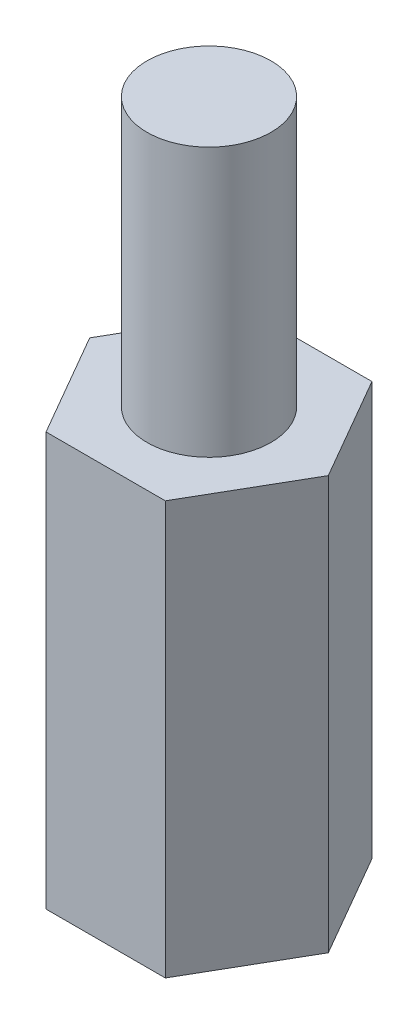
SolidWorks part; units mm, degrees
material "ﾅｲﾛﾝ 101"
ref_plane "正面" through (0, 0, 0) normal (0, 0, 1) x (1, 0, 0)
ref_plane "平面" through (0, 0, 0) normal (0, 1, 0) x (1, 0, 0)
ref_plane "右側面" through (0, 0, 0) normal (1, 0, 0) x (0, 0, -1)
sketch "ｽｹｯﾁ1" plane through (0, 0, 0) normal (0, 1, 0) x (1, 0, 0)
  line L1 (1.4434, -2.5) -> (2.8868, 0)
  line L2 (2.8868, 0) -> (1.4434, 2.5)
  line L3 (1.4434, 2.5) -> (-1.4434, 2.5)
  line L4 (-1.4434, 2.5) -> (-2.8868, 0)
  line L5 (-2.8868, 0) -> (-1.4434, -2.5)
  line L6 (-1.4434, -2.5) -> (1.4434, -2.5)
  circle A0 centre (0, 0) radius 2.5 construction
  dimension "D1" = 5
extrude "ﾎﾞｽ - 押し出し1" add sketch "ｽｹｯﾁ1" along normal blind 10
sketch "ｽｹｯﾁ2" plane through (0, 10, 0) normal (0, 1, 0) x (1, 0, 0)
  circle A0 centre (0, 0) radius 1.5
  dimension "D1" = 3
extrude "ﾎﾞｽ - 押し出し2" add sketch "ｽｹｯﾁ2" along normal blind 6.5
sketch "ｽｹｯﾁ3" plane through (0, 0, 0) normal (0, -1, 0) x (1, 0, 0)
  circle A0 centre (0, 0) radius 1.5
  dimension "D1" = 3
extrude "ｶｯﾄ - 押し出し1" cut sketch "ｽｹｯﾁ3" against normal blind 6.5
